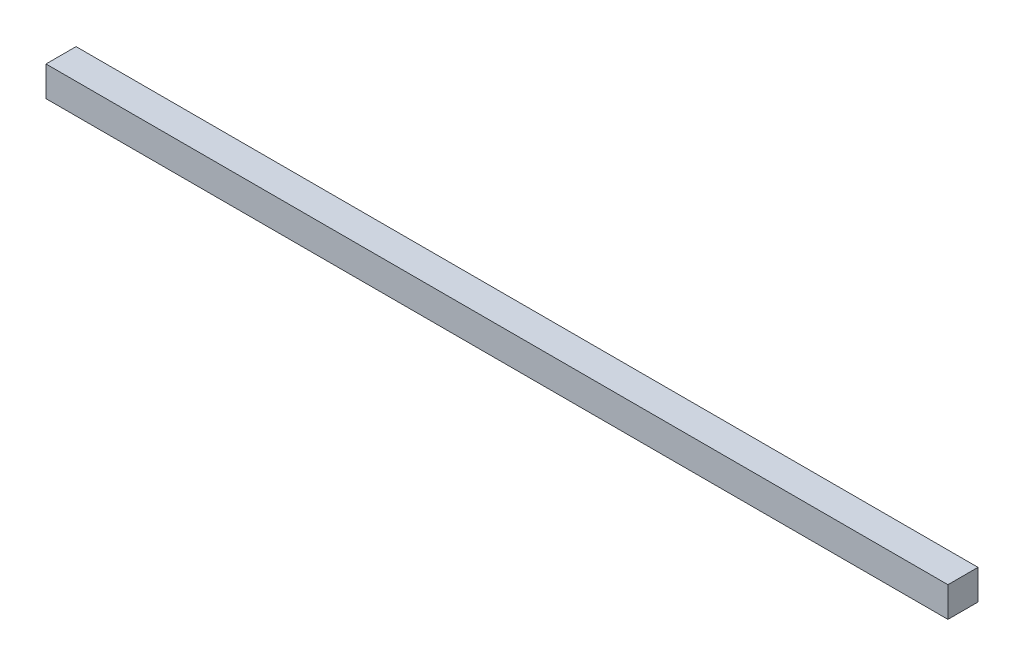
SolidWorks part; units mm, degrees
ref_plane "Front Plane" through (0, 0, 0) normal (0, 0, 1) x (1, 0, 0)
ref_plane "Top Plane" through (0, 0, 0) normal (0, 1, 0) x (1, 0, 0)
ref_plane "Right Plane" through (0, 0, 0) normal (1, 0, 0) x (0, 0, -1)
ref_plane "Plane1" through (0, 490, 0) normal (0, 1, 0) x (1, 0, 0)
sketch "Sketch1" plane through (0, 490, 0) normal (0, 1, 0) x (1, 0, 0)
  line L1 (180, -148) -> (420, -148)
  line L2 (180, -148) -> (180, -156)
  line L3 (180, -156) -> (420, -156)
  line L4 (420, -148) -> (420, -156)
extrude "Boss-Extrude1" add sketch "Sketch1" along normal blind 8
